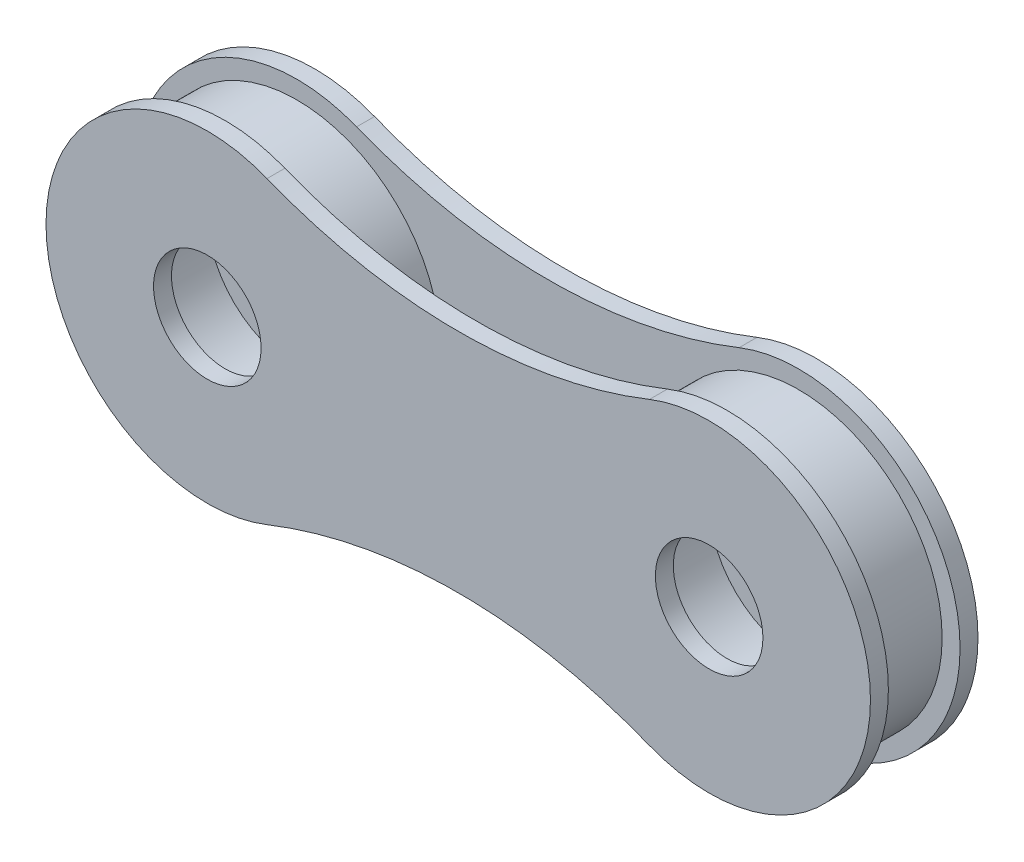
SolidWorks part; units mm, degrees
ref_plane "Front Plane" through (0, 0, 0) normal (0, 0, 1) x (1, 0, 0)
ref_plane "Top Plane" through (0, 0, 0) normal (0, 1, 0) x (1, 0, 0)
ref_plane "Right Plane" through (0, 0, 0) normal (1, 0, 0) x (0, 0, -1)
sketch "Sketch1" plane through (0, 0, 0) normal (0, 0, 1) x (1, 0, 0)
  line L0 (-14.8898, 0) -> (16.7447, 0) construction
  line L1 (-6.4421, 0) -> (-6.4421, 8.8457) construction
  line L2 (-0.4421, 0) -> (-0.4421, 8.8457) construction
  circle A0 centre (-10.4421, 0) radius 4
  circle A1 centre (3.5579, 0) radius 4
  circle A2 centre (-10.4421, 0) radius 2.5
  circle A3 centre (3.5579, 0) radius 2.5
  dimension "D1" = 8
  dimension "D2" = 5
  dimension "D3" = 8
  dimension "D4" = 5
  dimension "D5" = 6
extrude "Boss-Extrude1" add sketch "Sketch1" along normal mid plane 2
sketch "Sketch2" plane through (0, 0, 0) normal (0, 0, 1) x (1, 0, 0)
  line L0 (-0.9421, 0) -> (3.9116, 0) construction
  arc A0 (-8.7772, 4.1807) -> (-8.7772, -4.1807) centre (-10.4421, 0) ccw
  arc A1 (1.893, -4.1807) -> (1.893, 4.1807) centre (3.5579, 0) ccw
  arc A2 (-8.7772, 4.1807) -> (1.893, 4.1807) centre (-3.4421, 17.5771) ccw
  arc A3 (-8.7772, -4.1807) -> (1.893, -4.1807) centre (-3.4421, -17.5771) cw
  dimension "D1" = 9
  dimension "D2" = 9
extrude "Boss-Extrude2" add sketch "Sketch2" along normal blind 0.5 from offset 1
mirror "Mirror1" about plane through (0, 0, 0) normal (0, 0, 1) of "Boss-Extrude2"
sketch "Sketch4" plane through (0, 0, 0) normal (0, 0, 1) x (1, 0, 0)
  circle A0 centre (-10.4421, 0) radius 1.5
  circle A1 centre (3.5579, 0) radius 1.5
  dimension "D1" = 3
  dimension "D2" = 3
extrude "Cut-Extrude1" cut sketch "Sketch4" against normal through all both and the other way through all
